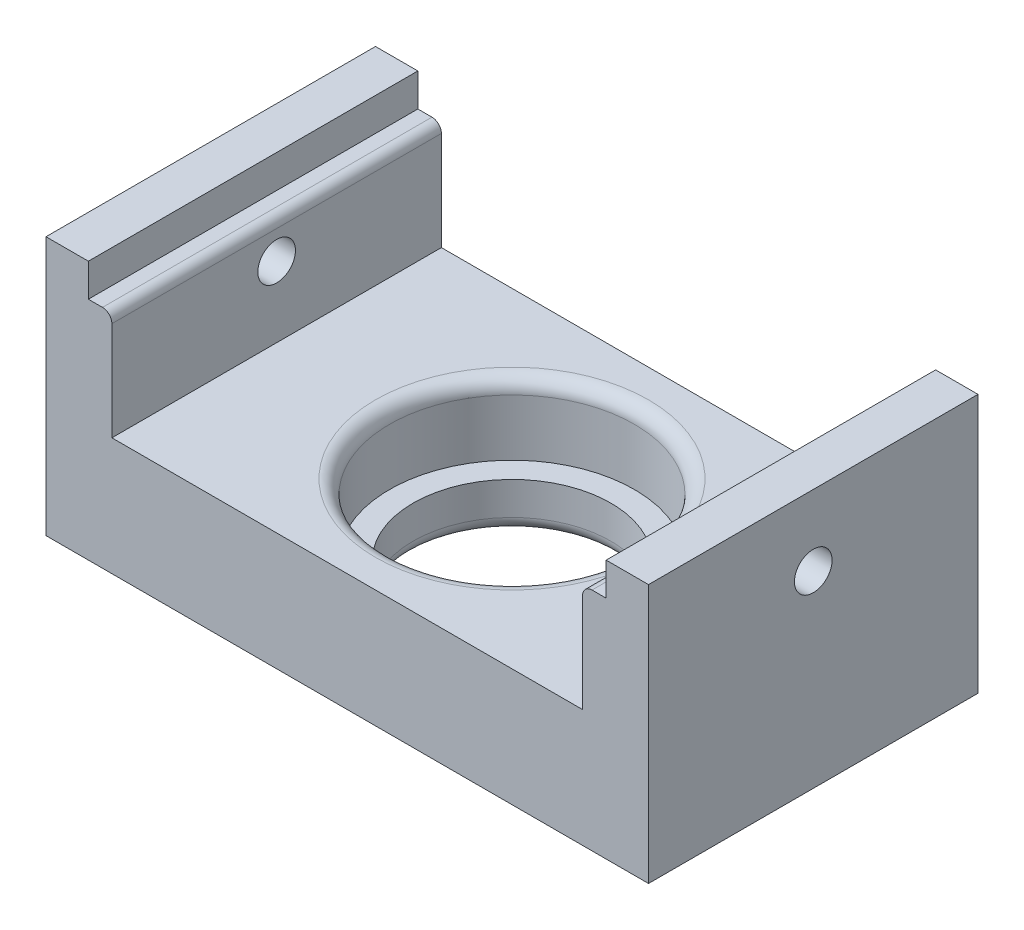
SolidWorks part; units mm, degrees
ref_plane "Front Plane" through (0, 0, 0) normal (0, 0, 1) x (1, 0, 0)
ref_plane "Top Plane" through (0, 0, 0) normal (0, 1, 0) x (1, 0, 0)
ref_plane "Right Plane" through (0, 0, 0) normal (1, 0, 0) x (0, 0, -1)
sketch "Szkic2" plane through (0, 0, 0) normal (0, 0, 1) x (1, 0, 0)
  line L0 (0, 10.5) -> (-32, 10.5)
  line L1 (-32, 10.5) -> (-32, -10.5)
  line L2 (-32, -10.5) -> (0, -10.5)
  line L3 (0, -10.5) -> (32, -10.5)
  line L4 (0, 10.5) -> (32, 10.5)
  line L5 (32, 10.5) -> (32, -10.5)
  line L7 (-32, 10.5) -> (32, 10.5)
  line L8 (-32, 10.5) -> (-32, 17.5)
  line L9 (-32, 17.5) -> (32, 17.5)
  line L10 (32, 10.5) -> (32, 17.5)
  line L11 (-32, -10.5) -> (32, -10.5)
  line L12 (-32, -10.5) -> (-32, -17.5)
  line L13 (-32, -17.5) -> (32, -17.5)
  line L14 (32, -10.5) -> (32, -17.5)
  circle A0 centre (0, 0) radius 10.5
  dimension "D1" = 21
  dimension "D2" = 32
  dimension "D3" = 32
  dimension "D4" = 7
  dimension "D5" = 7
extrude "Dodanie-wyciągnięcie1" add sketch "Szkic2" along normal blind 12.5 contours A0 L0 L1 L2 | A0 L3 L5 L4 | L4 L10 L9 L8 L0 | L14 L3 L2 L12 L13
sketch "Szkic3" plane through (0, 0, 12.5) normal (0, 0, 1) x (1, 0, 0)
  circle A0 centre (0, 0) radius 13
  dimension "D1" = 26
extrude "Wytnij-wyciągnięcie1" cut sketch "Szkic3" against normal blind 7.5
sketch "Szkic4" plane through (0, 0, 12.5) normal (0, 0, 1) x (1, 0, 0)
  line L0 (-32, -17.5) -> (32, -17.5) construction
  line L1 (-32, 17.5) -> (-25, 17.5)
  line L2 (-32, 17.5) -> (-32, -17.5)
  line L3 (-32, -17.5) -> (-25, -17.5)
  line L4 (-25, 17.5) -> (-25, -17.5)
  line L6 (32, 17.5) -> (25, 17.5)
  line L7 (32, 17.5) -> (32, -17.5)
  line L8 (32, -17.5) -> (25, -17.5)
  line L9 (25, 17.5) -> (25, -17.5)
  dimension "D1" = 7
  dimension "D2" = 7
extrude "Dodanie-wyciągnięcie2" add sketch "Szkic4" along normal blind 15
sketch "Szkic6" plane through (25, 0, 0) normal (-1, 0, 0) x (0, 0, 1)
  circle A0 centre (20, 0) radius 2
  dimension "D1" = 4
extrude "Wytnij-wyciągnięcie2" cut sketch "Szkic6" against normal blind 7 contours A0
sketch "Szkic7" plane through (-25, 0, 0) normal (1, 0, 0) x (0, 0, -1)
  circle A0 centre (-20, 0) radius 2
  dimension "D1" = 4
extrude "Wytnij-wyciągnięcie3" cut sketch "Szkic7" against normal blind 7 contours A0
fillet "Zaokrąglenie2" radius 1.5 1 edges at (13, 0, 12.5)
fillet "Zaokrąglenie3" radius 1.5 1 edges at (10.5, 0, 0)
sketch "Szkic8" plane through (0, 0, 27.5) normal (0, 0, 1) x (1, 0, 0)
  line L0 (-32, -17.5) -> (-25, -17.5) construction
  line L1 (-25, 17.5) -> (-27.5, 17.5)
  line L2 (-25, 17.5) -> (-25, -17.5)
  line L3 (-25, -17.5) -> (-27.5, -17.5)
  line L4 (-27.5, 17.5) -> (-27.5, -17.5)
  line L5 (25, -17.5) -> (32, -17.5) construction
  line L6 (25, 17.5) -> (27.5, 17.5)
  line L7 (25, 17.5) -> (25, -17.5)
  line L8 (25, -17.5) -> (27.5, -17.5)
  line L9 (27.5, 17.5) -> (27.5, -17.5)
  dimension "D1" = 2.5
  dimension "D2" = 2.5
extrude "Wytnij-wyciągnięcie4" cut sketch "Szkic8" against normal blind 3.5
fillet "Zaokrąglenie4" radius 1 2 edges at (25, 0, 24) (-25, 0, 24)
move or copy body "Obiekt-Przenieś/Kopiuj1" bodies to move or copy 106 copy no rotation origin (0, 0, 13.75) rotation axis (-1, 0, 0) rotation angle 90
